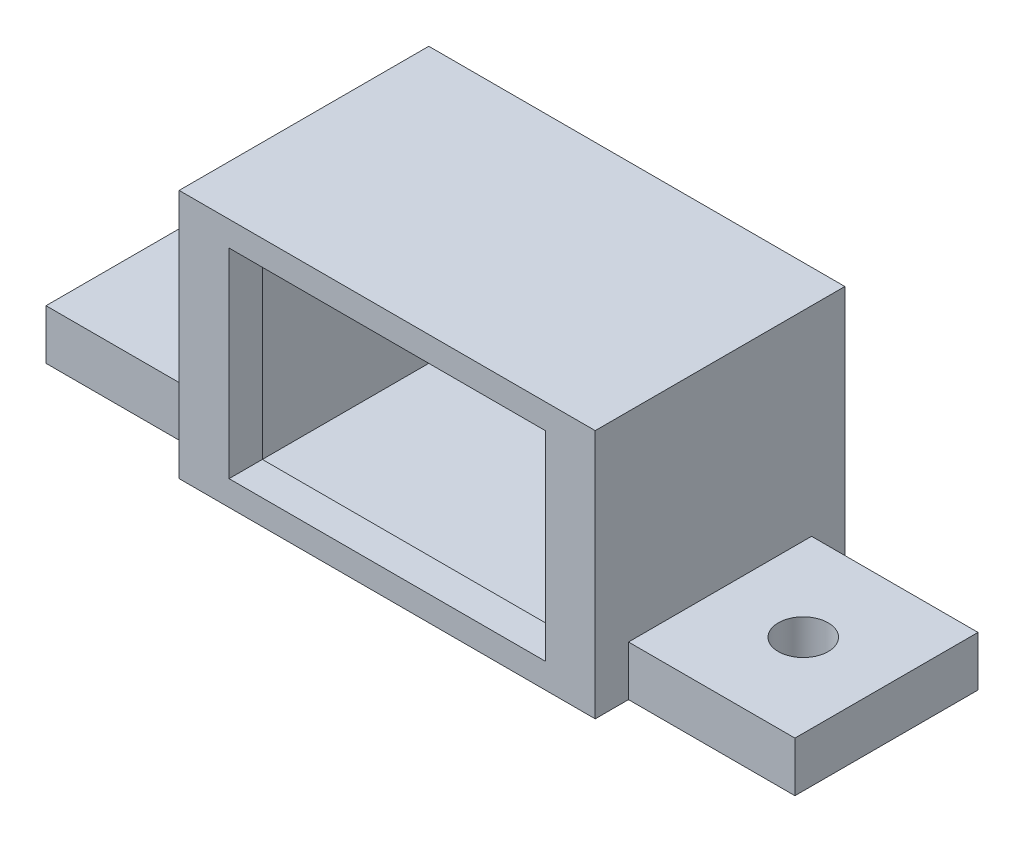
SolidWorks part; units mm, degrees
ref_plane "Front Plane" through (0, 0, 0) normal (0, 0, 1) x (1, 0, 0)
ref_plane "Top Plane" through (0, 0, 0) normal (0, 1, 0) x (1, 0, 0)
ref_plane "Right Plane" through (0, 0, 0) normal (1, 0, 0) x (0, 0, -1)
sketch "Sketch1" plane through (0, 0, 0) normal (0, 0, 1) x (1, 0, 0)
  line L0 (0, 0) -> (0, -15)
  line L1 (0, -15) -> (25, -15)
  line L2 (25, -15) -> (25, 0)
  line L3 (25, 0) -> (0, 0)
  dimension "D1" = 25
  dimension "D2" = 15
extrude "Boss-Extrude1" add sketch "Sketch1" along normal blind 15
sketch "Sketch2" plane through (0, 0, 0) normal (0, 0, -1) x (-1, 0, 0)
  line L0 (-12.5, 0) -> (-12.5, -15) construction
  line L1 (-25, 0) -> (0, 0) construction
  line L2 (0, -15) -> (-25, -15) construction
  line L3 (-25, -7.5) -> (0, -7.5) construction
  line L4 (-25, -15) -> (-25, 0) construction
  line L5 (0, 0) -> (0, -15) construction
  line L6 (-2.5, -1) -> (-22.5, -1)
  line L7 (-22.5, -1) -> (-22.5, -14)
  line L8 (-2.5, -1) -> (-2.5, -14)
  line L9 (-2.5, -14) -> (-22.5, -14)
  point P17 (-12.5, -1)
  point P18 (-2.5, -7.5)
  point P19 (-22.5, -7.5)
  dimension "D1" = 10
  dimension "D2" = 6.5
extrude "Cut-Extrude1" cut sketch "Sketch2" against normal blind 13
sketch "Sketch3" plane through (0, 0, 15) normal (0, 0, 1) x (1, 0, 0)
  line L0 (12.5, 0) -> (12.5, -15) construction
  line L1 (25, 0) -> (0, 0) construction
  line L2 (0, -15) -> (25, -15) construction
  line L3 (0, 0) -> (0, -15) construction
  line L4 (0, -7.5) -> (25, -7.5) construction
  line L5 (25, -15) -> (25, 0) construction
  line L6 (3, -13.5) -> (3, -1.5)
  line L7 (3, -1.5) -> (22, -1.5)
  line L8 (22, -1.5) -> (22, -13.5)
  line L9 (3, -13.5) -> (22, -13.5)
  point P17 (3, -7.5)
  point P18 (22, -7.5)
  dimension "D1" = 3
  dimension "D2" = 19
  dimension "D3" = 6
extrude "Cut-Extrude2" cut sketch "Sketch3" against normal through all
sketch "Sketch10" plane through (0, 0, 0) normal (-1, 0, 0) x (0, 0, 1)
  line L0 (7.5, -15) -> (7.5, 0) construction
  line L1 (15, -15) -> (0, -15) construction
  line L2 (15, 0) -> (0, 0) construction
  line L3 (2, -15) -> (2, -12)
  line L4 (2, -12) -> (13, -12)
  line L5 (2, -15) -> (13, -15)
  line L6 (13, -15) -> (13, -12)
  point P11 (7.5, -12)
  dimension "D1" = 3
  dimension "D2" = 5.5
extrude "Boss-Extrude5" add sketch "Sketch10" along normal blind 10
sketch "Sketch11" plane through (0, -12, 0) normal (0, 1, 0) x (1, 0, 0)
  line L0 (-10, -7.5) -> (0, -7.5) construction
  line L1 (-10, -13) -> (-10, -2) construction
  line L2 (0, -15) -> (0, 0) construction
  circle A0 centre (-5, -7.5) radius 1.5
extrude "Cut-Extrude4" cut sketch "Sketch11" against normal through all
sketch "Sketch13" plane through (25, 0, 0) normal (1, 0, 0) x (0, 0, -1)
  line L0 (-7.5, 0) -> (-7.5, -15) construction
  line L1 (-15, 0) -> (0, 0) construction
  line L2 (-15, -15) -> (0, -15) construction
  line L3 (-13, -15) -> (-13, -12)
  line L4 (-13, -12) -> (-2, -12)
  line L5 (-13, -15) -> (-2, -15)
  line L6 (-2, -15) -> (-2, -12)
  point P11 (-7.5, -12)
  dimension "D1" = 5.5
  dimension "D2" = 3
extrude "Boss-Extrude6" add sketch "Sketch13" along normal blind 10
sketch "Sketch14" plane through (0, -12, 0) normal (0, 1, 0) x (1, 0, 0)
  line L0 (30, -2) -> (30, -13) construction
  line L1 (35, -2) -> (25, -2) construction
  line L2 (35, -13) -> (25, -13) construction
  circle A0 centre (30, -7.5) radius 1.5
extrude "Cut-Extrude5" cut sketch "Sketch14" against normal through all
